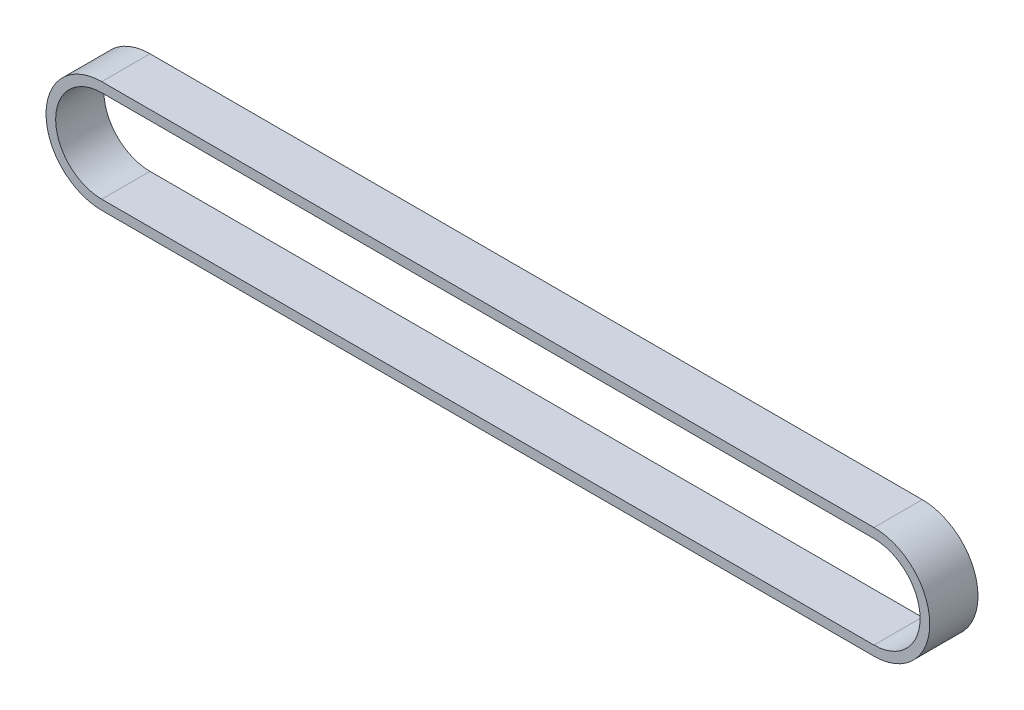
SolidWorks part; units mm, degrees
material "NEOPRENE"
ref_plane "Front" through (0, 0, 0) normal (0, 0, 1) x (1, 0, 0)
ref_plane "Top" through (0, 0, 0) normal (0, 1, 0) x (1, 0, 0)
ref_plane "Right" through (0, 0, 0) normal (1, 0, 0) x (0, 0, -1)
sketch "Sketch2" plane through (0, 0, 0) normal (0, 0, 1) x (1, 0, 0)
  line L0 (0, 0) -> (1, 0) construction
  line L1 (0, 0) -> (0, 1) construction
  line L2 (0, 14.325) -> (239.9967, 14.325)
  line L3 (239.9967, -14.325) -> (0, -14.325)
  arc A0 (0, -14.325) -> (0, 14.325) centre (0, 0) cw
  arc A1 (239.9967, 14.325) -> (239.9967, -14.325) centre (239.9967, 0) cw
extrude "Extrude-Thin1" add sketch "Sketch2" along normal mid plane 15 thin thin type one direction wall 3
